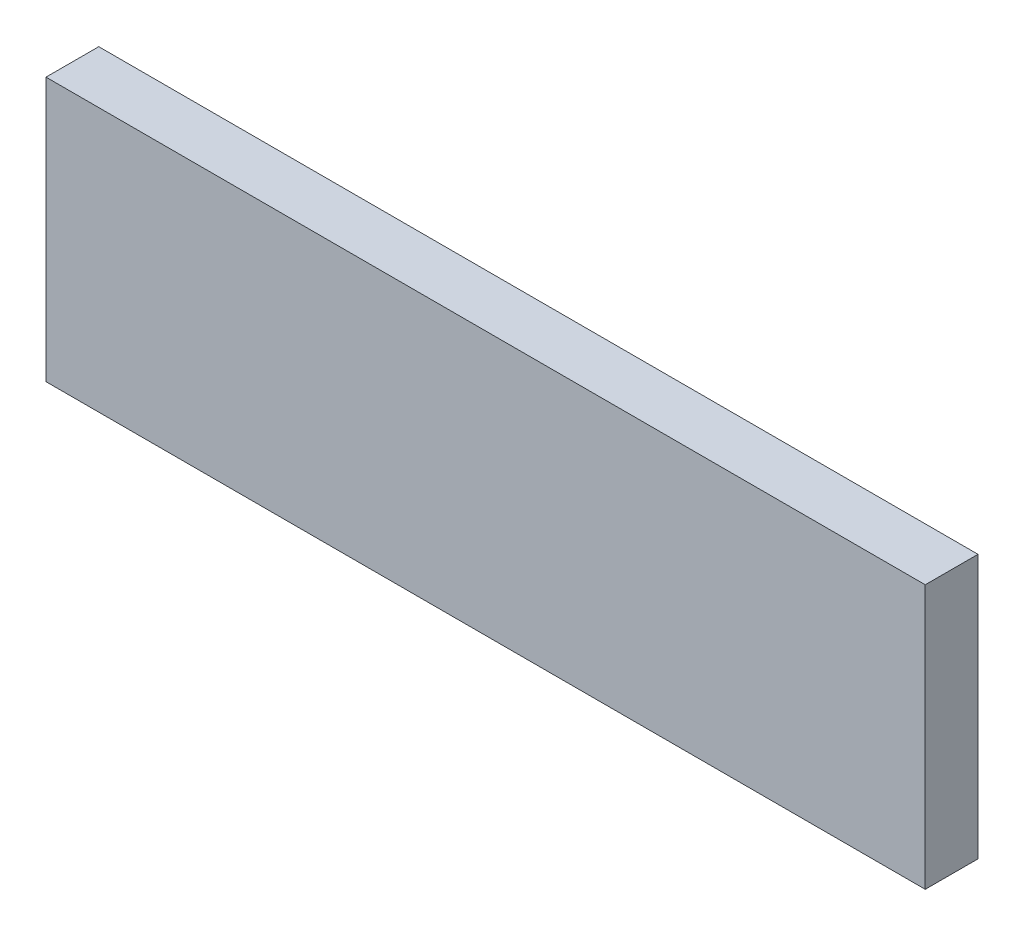
SolidWorks part; units mm, degrees
ref_plane "Front Plane" through (0, 0, 0) normal (0, 0, 1) x (1, 0, 0)
ref_plane "Top Plane" through (0, 0, 0) normal (0, 1, 0) x (1, 0, 0)
ref_plane "Right Plane" through (0, 0, 0) normal (1, 0, 0) x (0, 0, -1)
sketch "Sketch1" plane through (0, 0, 0) normal (0, 0, 1) x (1, 0, 0)
  line L1 (0, 0) -> (100, 0)
  line L2 (0, 0) -> (0, 30)
  line L3 (0, 30) -> (100, 30)
  line L4 (100, 0) -> (100, 30)
  dimension "D1" = 30
  dimension "D2" = 100
extrude "Boss-Extrude1" add sketch "Sketch1" along normal blind 6
